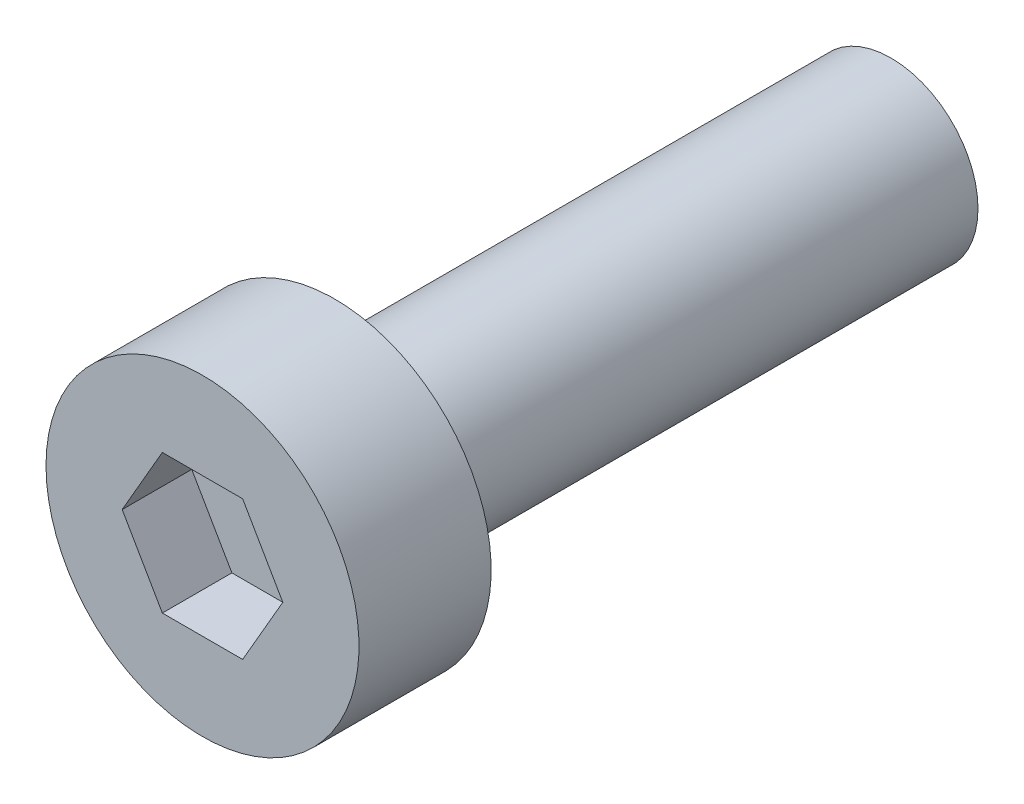
SolidWorks part; units mm, degrees
ref_plane "Plan de face" through (0, 0, 0) normal (0, 0, 1) x (1, 0, 0)
ref_plane "Plan de dessus" through (0, 0, 0) normal (0, 1, 0) x (1, 0, 0)
ref_plane "Plan de droite" through (0, 0, 0) normal (1, 0, 0) x (0, 0, -1)
sketch "Esquisse1" plane through (0, 0, 0) normal (0, 0, 1) x (1, 0, 0)
  circle A0 centre (0, 0) radius 1.25
  dimension "D1" = 2.5
extrude "Boss.-Extru.1" add sketch "Esquisse1" along normal blind 8
sketch "Esquisse2" plane through (0, 0, 8) normal (0, 0, 1) x (1, 0, 0)
  circle A0 centre (0, 0) radius 2.25
  dimension "D1" = 4.5
extrude "Boss.-Extru.2" add sketch "Esquisse2" along normal blind 1.9
sketch "Esquisse3" plane through (0, 0, 9.9) normal (0, 0, 1) x (1, 0, 0)
  line L1 (1.1547, 0) -> (0.5774, 1)
  line L2 (0.5774, 1) -> (-0.5774, 1)
  line L3 (-0.5774, 1) -> (-1.1547, 0)
  line L4 (-1.1547, 0) -> (-0.5774, -1)
  line L5 (-0.5774, -1) -> (0.5774, -1)
  line L6 (0.5774, -1) -> (1.1547, 0)
  circle A0 centre (0, 0) radius 1 construction
  dimension "D1" = 2
extrude "Enlèv. mat.-Extru.1" cut sketch "Esquisse3" against normal blind 1
